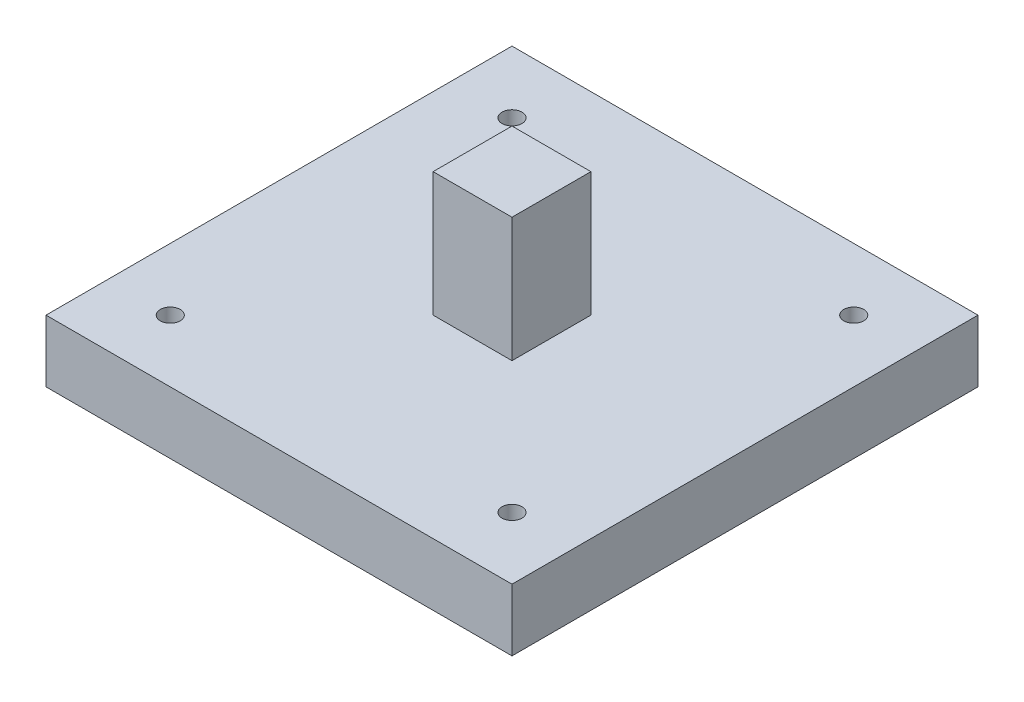
SolidWorks part; units mm, degrees
ref_plane "Спереди" through (0, 0, 0) normal (0, 0, 1) x (1, 0, 0)
ref_plane "Сверху" through (0, 0, 0) normal (0, 1, 0) x (1, 0, 0)
ref_plane "Справа" through (0, 0, 0) normal (1, 0, 0) x (0, 0, -1)
other "Configuration Table"
sketch "Эскиз1" plane through (0, 0, 0) normal (0, 1, 0) x (1, 0, 0)
  line L1 (-35.2387, 29.2085) -> (39.7613, 29.2085)
  line L2 (-35.2387, 29.2085) -> (-35.2387, -45.7915)
  line L3 (-35.2387, -45.7915) -> (39.7613, -45.7915)
  line L4 (39.7613, 29.2085) -> (39.7613, -45.7915)
  dimension "D1" = 75
extrude "Бобышка-Вытянуть1" add sketch "Эскиз1" along normal blind 10
sketch "Эскиз2" plane through (0, 10, 0) normal (0, 1, 0) x (1, 0, 0)
  line L0 (-25.2387, 29.2085) -> (-25.2387, -45.7915)
  line L1 (29.7613, 29.2085) -> (29.7613, -45.7915)
  line L2 (-35.2387, 19.2085) -> (39.7613, 19.2085)
  line L3 (-35.2387, -35.7915) -> (39.7613, -35.7915)
  line L4 (39.7613, -45.7915) -> (39.7613, 29.2085) construction
  line L5 (-35.2387, 29.2085) -> (-35.2387, -45.7915) construction
  line L6 (39.7613, 29.2085) -> (-35.2387, 29.2085) construction
  line L7 (-35.2387, -45.7915) -> (39.7613, -45.7915) construction
  circle A0 centre (-25.2387, 19.2085) radius 1.6
  circle A1 centre (29.7613, 19.2085) radius 1.6
  circle A2 centre (-25.2387, -35.7915) radius 1.6
  circle A3 centre (29.7613, -35.7915) radius 1.6
  point P22 (0, 0)
  point P28 (0, 0)
  point P29 (0, 0)
  dimension "D5" = 3.2
  dimension "D1" = 10
  dimension "D2" = 10
  dimension "D3" = 10
  dimension "D4" = 10
extrude "Вырез-Вытянуть1" cut sketch "Эскиз2" against normal blind 10 contours A0 | A1 | A2 | A3
sketch "Эскиз3" plane through (0, 10, 0) normal (0, 1, 0) x (1, 0, 0)
  line L0 (2.2613, 29.2085) -> (2.2613, -45.7915)
  line L1 (-4.0887, -1.9415) -> (8.6113, -1.9415)
  line L2 (-4.0887, -1.9415) -> (-4.0887, -14.6415)
  line L3 (-4.0887, -14.6415) -> (8.6113, -14.6415)
  line L4 (8.6113, -1.9415) -> (8.6113, -14.6415)
  line L5 (-35.2387, -45.7915) -> (39.7613, -45.7915) construction
  line L7 (39.7613, 29.2085) -> (-35.2387, 29.2085) construction
  line L8 (-35.2387, -8.2915) -> (39.7613, -8.2915)
  line L9 (39.7613, -45.7915) -> (39.7613, 29.2085) construction
  line L10 (-35.2387, 29.2085) -> (-35.2387, -45.7915) construction
  point P11 (2.2613, -14.6415)
  point P15 (0, 0)
  point P18 (8.6113, -8.2915)
  dimension "D1" = 12.7
extrude "Бобышка-Вытянуть2" add sketch "Эскиз3" along normal blind 20 contours L1 L4 L3 L2
